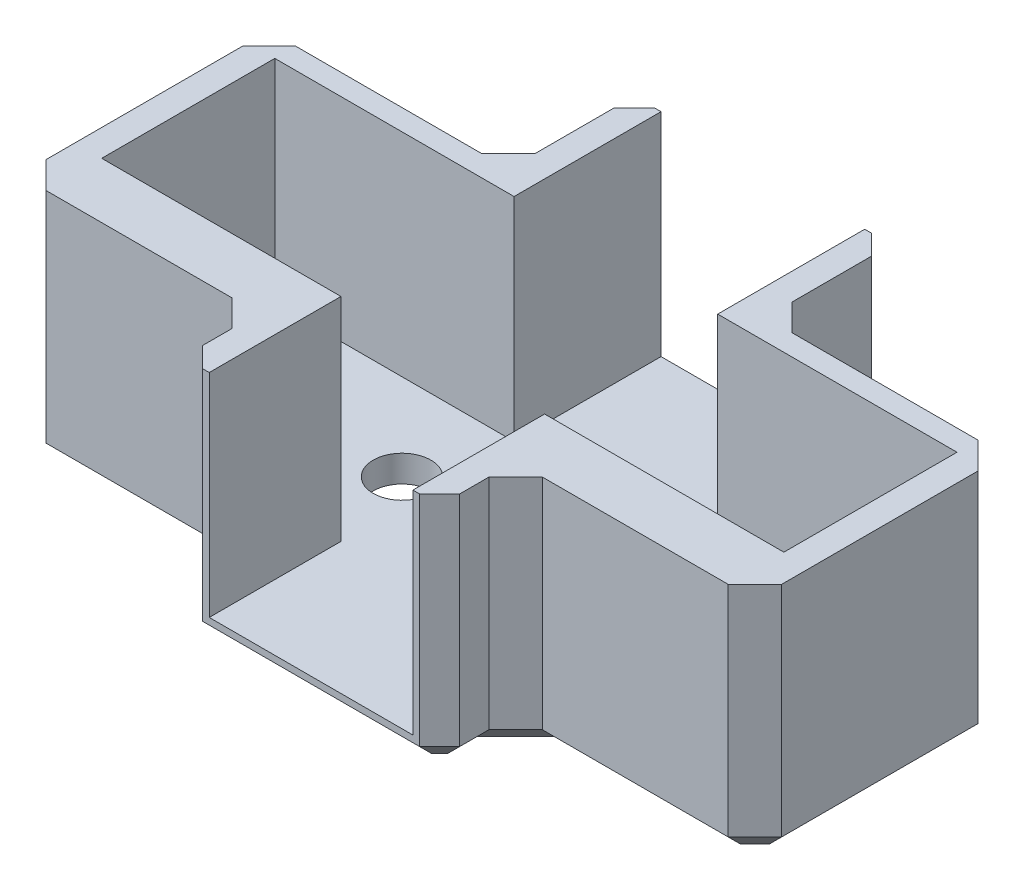
SolidWorks part; units mm, degrees
ref_plane "Front Plane" through (0, 0, 0) normal (0, 0, 1) x (1, 0, 0)
ref_plane "Top Plane" through (0, 0, 0) normal (0, 1, 0) x (1, 0, 0)
ref_plane "Right Plane" through (0, 0, 0) normal (1, 0, 0) x (0, 0, -1)
sketch "Sketch1" plane through (0, 0, 0) normal (0, 1, 0) x (1, 0, 0)
  line L0 (17.9835, 31.5337) -> (17.9835, 22.5337) construction
  line L9 (17.9835, 22.5337) -> (0.0765, 22.5337) construction
  line L10 (0.0765, 22.5337) -> (0.0765, 9.5797) construction
  line L19 (0.0765, 9.5797) -> (17.9835, 9.5797) construction
  line L20 (17.9835, 9.5797) -> (17.9835, 1.722) construction
  line L29 (17.9835, 1.722) -> (33.2235, 1.722) construction
  line L30 (33.2235, 1.722) -> (33.2235, 9.5797) construction
  line L31 (33.2235, 9.5797) -> (51.1305, 9.5797) construction
  line L32 (51.1305, 9.5797) -> (51.1305, 22.5337) construction
  line L33 (51.1305, 22.5337) -> (33.2235, 22.5337) construction
  line L34 (33.2235, 22.5337) -> (33.2235, 31.5337) construction
  line L35 (33.2235, 31.5337) -> (17.9835, 31.5337) construction
  line L36 (35.1285, 16.0567) -> (35.1285, 22.5337) construction
  line L37 (16.0785, 16.0567) -> (16.0785, 9.5797) construction
  line L38 (16.0785, 16.0567) -> (0.0765, 16.0567) construction
  line L39 (35.1285, 16.0567) -> (51.1305, 16.0567) construction
  line L40 (35.2235, 33.5337) -> (15.9835, 33.5337)
  line L41 (15.9835, 33.5337) -> (15.9835, 24.1072)
  line L42 (15.9835, 24.1072) -> (-1.9235, 24.1072)
  line L43 (-1.9235, 24.1072) -> (-1.9235, 5.4113)
  line L44 (-1.9235, 5.4113) -> (15.9835, 5.4113)
  line L45 (15.9835, 5.4113) -> (15.9835, -0.278)
  line L46 (15.9835, -0.278) -> (35.2235, -0.278)
  line L47 (35.2235, -0.278) -> (35.2235, 5.4113)
  line L48 (35.2235, 5.4113) -> (53.1305, 5.4113)
  line L49 (53.1305, 5.4113) -> (53.1305, 24.1072)
  line L50 (53.1305, 24.1072) -> (35.2235, 24.1072)
  line L51 (35.2235, 24.1072) -> (35.2235, 33.5337)
  circle A0 centre (16.0785, 16.0567) radius 2.159
  circle A1 centre (35.1285, 16.0567) radius 2.159
  dimension "D3" = 12.954
  dimension "D4" = 9
  dimension "D1" = 15.24
  dimension "D2" = 51.054
  dimension "D5" = 4.1684
  dimension "D6" = 1.5735
  dimension "D7" = 2
  dimension "D8" = 2
  dimension "D9" = 19.05
  dimension "D10" = 7.8577
extrude "Boss-Extrude1" add sketch "Sketch1" along normal blind 2
sketch "Sketch3" plane through (0, 2, 0) normal (0, 1, 0) x (1, 0, 0)
  line L0 (33.2235, 30.8179) -> (33.2235, 33.5337)
  line L1 (35.2235, 33.5337) -> (15.9835, 33.5337) construction
  line L2 (33.2235, 1.722) -> (33.2235, -0.278)
  line L3 (15.9835, -0.278) -> (35.2235, -0.278) construction
  line L4 (33.2235, 33.5337) -> (35.2235, 33.5337)
  line L5 (35.2235, 33.5337) -> (35.2235, 24.1072)
  line L6 (35.2235, 24.1072) -> (53.1305, 24.1072)
  line L7 (53.1305, 24.1072) -> (53.1305, 5.4113)
  line L8 (53.1305, 5.4113) -> (35.2235, 5.4113)
  line L9 (35.2235, 5.4113) -> (35.2235, -0.278)
  line L10 (35.2235, -0.278) -> (33.2235, -0.278)
  line L11 (17.9835, 1.722) -> (17.9835, -0.278)
  line L12 (17.9835, -0.278) -> (15.9835, -0.278)
  line L13 (15.9835, -0.278) -> (15.9835, 5.4113)
  line L14 (15.9835, 5.4113) -> (-1.9235, 5.4113)
  line L15 (-1.9235, 5.4113) -> (-1.9235, 24.1072)
  line L16 (-1.9235, 24.1072) -> (15.9835, 24.1072)
  line L17 (15.9835, 24.1072) -> (15.9835, 33.5337)
  line L18 (15.9835, 33.5337) -> (17.9835, 33.5337)
  line L19 (17.9835, 33.5337) -> (17.9835, 29.0407)
  line L20 (0.0765, 16.0567) -> (16.0785, 16.0567) construction
  line L36 (33.2235, 22.5337) -> (33.2235, 30.8179)
  line L38 (17.9835, 29.0407) -> (17.9835, 22.5337)
  line L39 (17.9835, 22.5337) -> (0.0765, 22.5337)
  line L40 (0.0765, 22.5337) -> (0.0765, 9.5797)
  line L41 (0.0765, 9.5797) -> (17.9835, 9.5797)
  line L42 (17.9835, 9.5797) -> (17.9835, 1.722)
  line L44 (33.2235, 1.722) -> (33.2235, 9.5797)
  line L45 (33.2235, 9.5797) -> (51.1305, 9.5797)
  line L46 (51.1305, 9.5797) -> (51.1305, 22.5337)
  line L47 (51.1305, 22.5337) -> (33.2235, 22.5337)
  dimension "D2" = 2
  dimension "D1" = 12.954
  dimension "D3" = 2
  dimension "D4" = 2
  dimension "D5" = 2
  dimension "D6" = 2
  dimension "D7" = 2
extrude "Boss-Extrude2" add sketch "Sketch3" along normal blind 15.875
chamfer "Chamfer1" distance 2 angle 45 4 edges at (53.1305, 8.9375, -5.4113) (53.1305, 8.9375, -24.1072) (-1.9235, 8.9375, -24.1072) (-1.9235, 8.9375, -5.4113)
chamfer "Chamfer2" distance 2 angle 45 4 edges at (35.2235, 8.9375, -5.4113) (15.9835, 8.9375, -5.4113) (15.9835, 8.9375, -24.1072) (35.2235, 8.9375, -24.1072)
chamfer "Chamfer3" distance 1.5 angle 45 2 edges at (15.9835, 8.9375, -33.5337) (35.2235, 8.9375, -33.5337)
chamfer "Chamfer4" distance 1.5 angle 45 2 edges at (15.9835, 8.9375, 0.278) (35.2235, 8.9375, 0.278)
chamfer "Chamfer5" distance 1.5 angle 45 24 edges at (34.4735, 0, -0.472) (35.2235, 0, -2.3166) (36.2235, 0, -4.4113) (44.177, 0, -5.4113) (52.1305, 0, -6.4113) (53.1305, 0, -14.7592) (52.1305, 0, -23.1072) (44.177, 0, -24.1072) (36.2235, 0, -25.1072) (35.2235, 0, -29.0704) (34.4735, 0, -32.7837) (25.6035, 0, -33.5337) (16.7335, 0, -32.7837) (15.9835, 0, -29.0704) (14.9835, 0, -25.1072) (7.03, 0, -24.1072) (-0.9235, 0, -23.1072) (-1.9235, 0, -14.7592) (-0.9235, 0, -6.4113) (7.03, 0, -5.4113) (14.9835, 0, -4.4113) (15.9835, 0, -2.3166) (16.7335, 0, -0.472) (25.6035, 0, 0.278)
